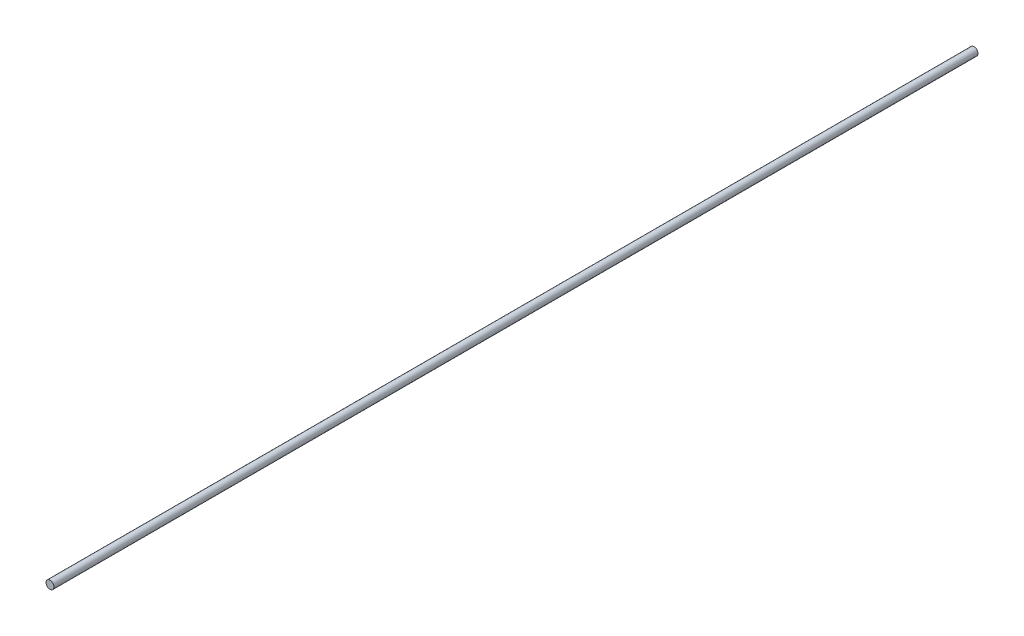
SolidWorks part; units mm, degrees
ref_plane "前视基准面" through (0, 0, 0) normal (0, 0, 1) x (1, 0, 0)
ref_plane "上视基准面" through (0, 0, 0) normal (0, 1, 0) x (1, 0, 0)
ref_plane "右视基准面" through (0, 0, 0) normal (1, 0, 0) x (0, 0, -1)
other "Configuration Table"
sketch "草图1" plane through (0, 0, 0) normal (0, 0, 1) x (1, 0, 0)
  circle A0 centre (0, 0) radius 0.4
extrude "D0p8钢索直线跨度" add sketch "草图1" along normal blind 93.3538
